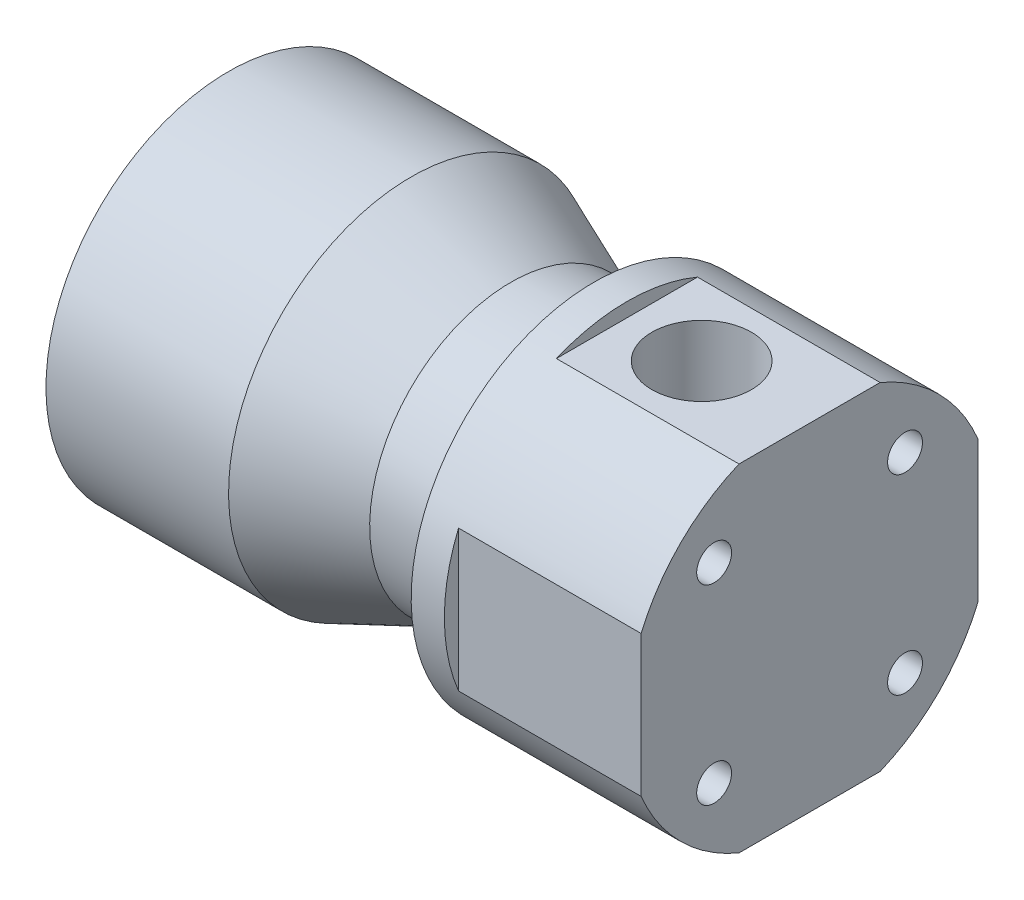
SolidWorks part; units mm, degrees
ref_plane "Front Plane" through (0, 0, 0) normal (1, 0, 0) x (0, 1, 0)
ref_plane "Top Plane" through (0, 0, 0) normal (0, 0, 1) x (0, 1, 0)
ref_plane "Right Plane" through (0, 0, 0) normal (0, 1, 0) x (-1, 0, 0)
sketch "Sketch1" plane through (0, 0, 0) normal (0, 0, 1) x (0, 1, 0)
  line L0 (0, 70) -> (0, -108.3327) construction
  line L1 (0, 0) -> (22, 0)
  line L2 (22, 0) -> (22, 26)
  line L3 (22, 26) -> (17, 26)
  line L4 (17, 26) -> (17, 36)
  line L5 (17, 36) -> (22, 48)
  line L6 (22, 48) -> (22, 70)
  line L7 (22, 70) -> (0, 70)
  line L8 (0, 70) -> (0, 0)
  dimension "D1" = 22
  dimension "D2" = 26
  dimension "D3" = 5
  dimension "D4" = 22
  dimension "D5" = 22
  dimension "D6" = 10
  dimension "D7" = 70
revolve "Revolve1" add sketch "Sketch1" angle 360 about L0
sketch "Sketch2" plane through (0, 0, 0) normal (1, 0, 0) x (0, 1, 0)
  line L0 (0, 0) -> (0, 23.604) construction
  line L1 (0, 0) -> (-24.4837, 0) construction
  line L2 (-8.5, 20.2916) -> (8.5, 20.2916)
  line L3 (20.2916, 8.5) -> (20.2916, -8.5)
  line L4 (8.5, -20.2916) -> (-8.5, -20.2916)
  line L5 (-20.2916, -8.5) -> (-20.2916, 8.5)
  circle A0 centre (-11.5, 11.5) radius 2.1
  circle A1 centre (11.5, 11.5) radius 2.1
  circle A2 centre (11.5, -11.5) radius 2.1
  circle A3 centre (-11.5, -11.5) radius 2.1
  circle A4 centre (0, 0) radius 22 construction
  arc A5 (-20.2916, 8.5) -> (-20.2916, -8.5) centre (0, 0) ccw
  arc A6 (8.5, 20.2916) -> (-8.5, 20.2916) centre (0, 0) ccw
  arc A7 (20.2916, -8.5) -> (20.2916, 8.5) centre (0, 0) ccw
  arc A8 (-8.5, -20.2916) -> (8.5, -20.2916) centre (0, 0) ccw
  point P25 (0, 0)
  dimension "D1" = 4.2
  dimension "D2" = 11.5
  dimension "D3" = 11.5
  dimension "D6" = 17
  dimension "D4" = 2
  dimension "D5" = 2
  dimension "D7" = 4
extrude "Cut-Extrude1" cut sketch "Sketch2" against normal blind 22
sketch "Sketch3" plane through (0, 20.2916, 0) normal (0, 1, 0) x (-1, 0, 0)
  line L0 (0, 8.5) -> (0, -8.5) construction
  circle A0 centre (13, 0) radius 6
  dimension "D2" = 12
  dimension "D1" = 13
extrude "Cut-Extrude2" cut sketch "Sketch3" against normal up to next
